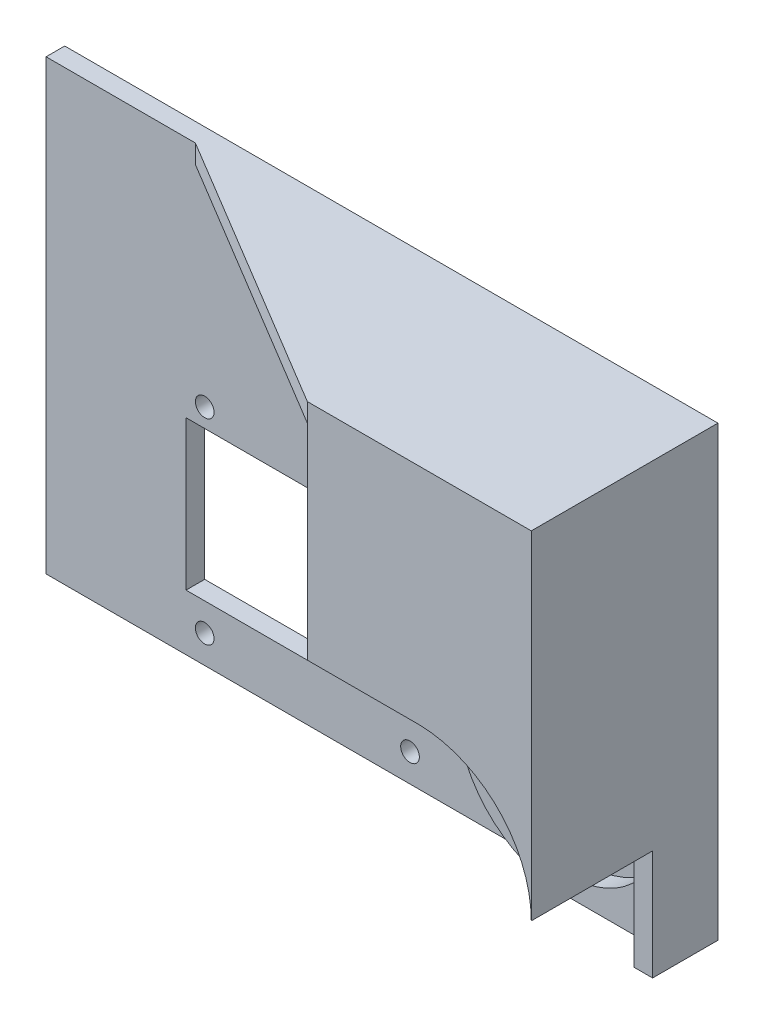
SolidWorks part; units mm, degrees
ref_plane "Front Plane" through (0, 0, 0) normal (0, 0, 1) x (1, 0, 0)
ref_plane "Top Plane" through (0, 0, 0) normal (0, 1, 0) x (1, 0, 0)
ref_plane "Right Plane" through (0, 0, 0) normal (1, 0, 0) x (0, 0, -1)
sketch "Sketch1" plane through (0, 0, 0) normal (0, 0, 1) x (1, 0, 0)
  line L1 (0, 0) -> (58, 0)
  line L2 (0, 0) -> (0, -48)
  line L3 (0, -48) -> (58, -48)
  line L4 (58, 0) -> (58, -48)
  dimension "D1" = 58
  dimension "D2" = 48
extrude "Boss-Extrude1" add sketch "Sketch1" along normal blind 2
sketch "Sketch2" plane through (0, 0, 2) normal (0, 0, 1) x (1, 0, 0)
  line L0 (0, -48) -> (5, -48) construction
  line L1 (0, -48) -> (58, -48) construction
  line L2 (5, -48) -> (5, -45) construction
  line L3 (5, -45) -> (27, -45) construction
  line L4 (5, -45) -> (5, -24) construction
  line L5 (5, -24) -> (27, -24) construction
  line L6 (0, 0) -> (0, -48) construction
  line L7 (3, -42) -> (30, -42)
  line L8 (3, -42) -> (3, -26)
  line L9 (3, -26) -> (30, -26)
  line L10 (30, -42) -> (30, -26)
  circle A0 centre (5, -45) radius 1
  circle A1 centre (27, -45) radius 1
  circle A2 centre (5, -24) radius 1
  circle A3 centre (27, -24) radius 1
  dimension "D3" = 2
  dimension "D7" = 2
  dimension "D8" = 2
  dimension "D9" = 2
  dimension "D1" = 5
  dimension "D2" = 3
  dimension "D4" = 22
  dimension "D5" = 21
  dimension "D6" = 22
  dimension "D10" = 3
  dimension "D11" = 6
  dimension "D12" = 27
  dimension "D13" = 16
extrude "Cut-Extrude1" cut sketch "Sketch2" against normal blind 2
sketch "Sketch3" plane through (0, 0, 2) normal (0, 0, 1) x (1, 0, 0)
  line L0 (0, 0) -> (4, 0) construction
  line L1 (58, 0) -> (0, 0) construction
  line L2 (58, -48) -> (58, 0) construction
  line L3 (4, 0) -> (58, 0)
  line L4 (4, 0) -> (4, -2)
  line L5 (4, -2) -> (58, -2)
  line L6 (58, 0) -> (58, -2)
  dimension "D1" = 4
  dimension "D2" = 2
extrude "Boss-Extrude2" add sketch "Sketch3" along normal blind 18
sketch "Sketch4" plane through (0, 0, 0) normal (0, 1, 0) x (1, 0, 0)
  line L0 (58, -20) -> (34, -20) construction
  line L1 (58, -20) -> (4, -20) construction
  line L2 (4, -2) -> (34, -20)
  line L3 (34, -20) -> (4, -20)
  line L4 (4, -20) -> (4, -2)
  dimension "D1" = 24
extrude "Cut-Extrude2" cut sketch "Sketch4" against normal blind 2
sketch "Sketch5" plane through (0, -2, 0) normal (0, -1, 0) x (1, 0, 0)
  line L0 (0, 2) -> (58, 2) construction
  line L1 (58, 20) -> (34, 20)
  line L2 (58, 20) -> (58, 18)
  line L4 (34, 20) -> (34, 18)
  line L9 (56, 18) -> (34, 18)
  line L11 (58, 18) -> (58, 2)
  line L12 (58, 2) -> (56, 2)
  line L13 (56, 18) -> (56, 2)
  dimension "D1" = 24
  dimension "D2" = 2
  dimension "D3" = 2
extrude "Boss-Extrude3" add sketch "Sketch5" along normal blind 46
sketch "Sketch6" plane through (0, 0, 2) normal (0, 0, 1) x (1, 0, 0)
  line L0 (58, -48) -> (34, -48) construction
  line L1 (58, -48) -> (34, -48) construction
  line L2 (34, -48) -> (34, -36.2) construction
  line L3 (34, -36.2) -> (36, -36.2) construction
  line L4 (58, -42.7437) -> (46, -42.7437) construction
  line L5 (58, -48) -> (58, 0) construction
  line L6 (36, -36.2) -> (34, -36.2)
  line L7 (58, -36.2) -> (56, -36.2) construction
  line L8 (46, -46) -> (46, -48) construction
  line L9 (56, -36.2) -> (57, -36.2)
  line L10 (57, -36.2) -> (57, -48)
  line L11 (57, -48) -> (46, -48)
  arc A0 (34, -36.2) -> (46, -48) centre (45.8017, -36.2) ccw
  arc A1 (36, -36.2) -> (56, -36.2) centre (46, -35.998) ccw
  dimension "D1" = 24
  dimension "D2" = 11.8
  dimension "D3" = 2
  dimension "D4" = 12
  dimension "D5" = 2
  dimension "D6" = 2
extrude "Boss-Extrude4" add sketch "Sketch6" along normal blind 2
sketch "Sketch7" plane through (0, 0, 20) normal (0, 0, 1) x (1, 0, 0)
  line L0 (58, -48) -> (58, -36.2)
  line L1 (58, -48) -> (58, 0) construction
  line L2 (58, -48) -> (34, -48)
  line L3 (34, -48) -> (34, -24)
  line L4 (34, -48) -> (34, -2) construction
  line L5 (34, -24) -> (46, -24)
  arc A0 (46, -24) -> (58, -36.2) centre (45.7983, -36.2) cw
  dimension "D1" = 11.8
  dimension "D2" = 24
  dimension "D3" = 12
extrude "Cut-Extrude3" cut sketch "Sketch7" against normal blind 13
sketch "Sketch8" plane through (0, 0, 0) normal (-1, 0, 0) x (0, 0, 1)
  line L1 (0, 0) -> (2, 0)
  line L2 (0, 0) -> (0, -48)
  line L3 (0, -48) -> (2, -48)
  line L4 (2, 0) -> (2, -48)
extrude "Boss-Extrude5" add sketch "Sketch8" along normal blind 12
